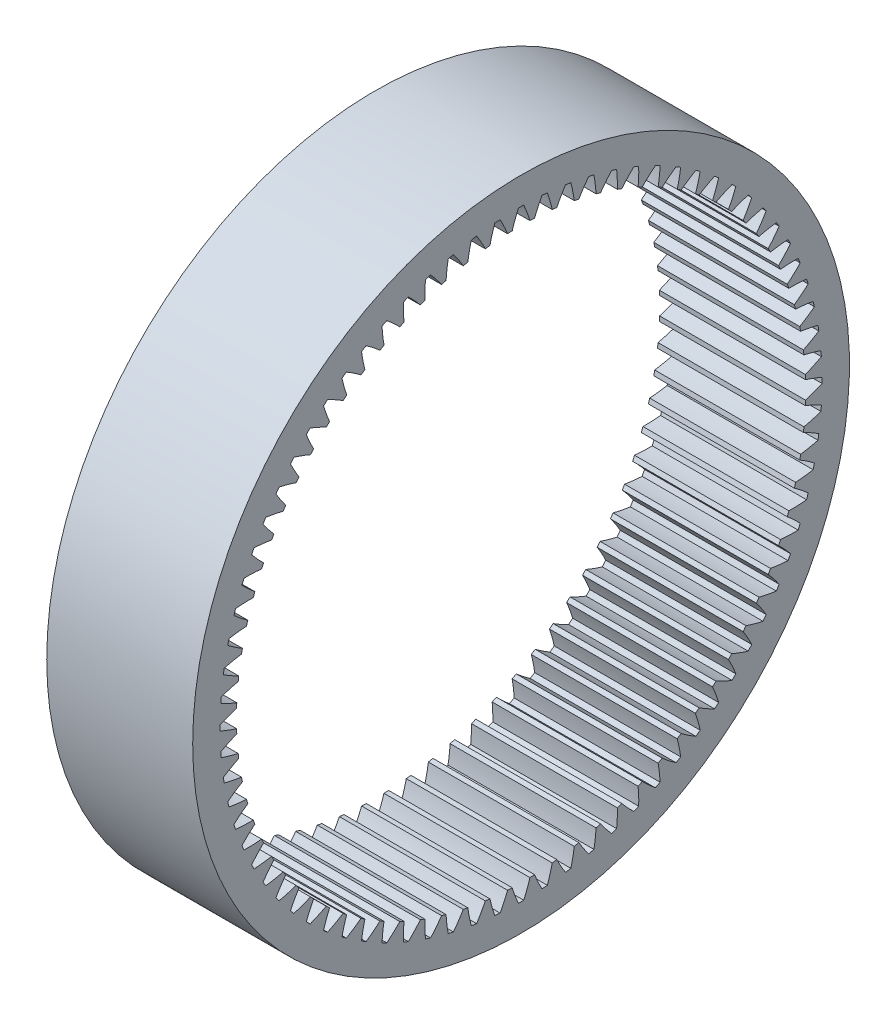
SolidWorks part; units mm, degrees
ref_plane "Plane1" through (0, 0, 0) normal (0, 0, 1) x (1, 0, 0)
ref_plane "Plane2" through (0, 0, 0) normal (0, 1, 0) x (1, 0, 0)
ref_plane "Plane3" through (0, 0, 0) normal (1, 0, 0) x (0, 0, -1)
other "Configuration Table"
sketch "HoldingSke" plane through (0, 0, 0) normal (0, 1, 0) x (1, 0, 0)
  line L0 (0, 0) -> (0.1158, -0.6565)
  line L1 (-15, 0) -> (100, 0) construction
  line L2 (0, 0) -> (-2.1039, 2.3779)
  line L3 (0, 0) -> (-11.863, 4.5341)
  line L4 (0, 0) -> (1.4996, 8.5048)
  line L5 (0, 0) -> (-23.7986, -8.8762)
  line L6 (0, 0) -> (-10.5278, -7.1032)
  line L7 (-2.1039, 2.3779) -> (3.3635, 27.1825)
  line L8 (-76.2, 3.8779) -> (-54.61, 3.8779)
  line L9 (-71.009, 38.7566) -> (-53.1078, 45.2721)
  line L10 (-76.2, 71.12) -> (104.1128, 71.12)
  line L11 (0, 0) -> (-30, 0)
  line L12 (-76.2, 101.6) -> (-76.147, 101.6)
  line L13 (24.9733, 27.94) -> (52.9518, 28.4284)
  line L14 (24.9733, 27.94) -> (24.9743, 27.94)
  line L15 (24.9733, 27.94) -> (100.4006, 29.5858)
  circle A0 centre (0, 0) radius 67.5
  circle A1 centre (0, 0) radius 12.7
  circle A2 centre (0, 0) radius 12.7
  dimension "MHD" = 25.4
  dimension "Hub_dia" = 25.4
  dimension "Diameter" = 135
  dimension "Num_teeth" = 80
  dimension "Pitch" = 0.6667
  dimension "Overall_len" = 25.4
  dimension "Show_teeth" = 80
  dimension "Thickness" = 12.7
  dimension "OAL" = 25.4001
  dimension "T_dim" = 21.59
  dimension "Ap" = 20
  dimension "H" = 19.05
  dimension "Pitch_radius" = 180.3128
  dimension "Width" = 30
  dimension "Backlash" = 0.053
  dimension "Addendum_fac" = 1
  dimension "Dedendum_fac" = 1.25
  dimension "Clearance_fac" = 0.25
  dimension "Dedendum_add" = 0.001
  dimension "Module" = 1.5
sketch "BasProSke" plane through (0, 0, 0) normal (0, 1, 0) x (1, 0, 0)
  line L0 (-10, 0) -> (60, 0) construction
  line L1 (0, 58.5) -> (0, 67.5)
  line L2 (0, 58.5) -> (30, 58.5)
  line L3 (30, 58.5) -> (30, 67.5)
  line L4 (30, 67.5) -> (0, 67.5)
  dimension "Diameter" = 135
  dimension "Thickness" = 30
  dimension "Inside_diameter" = 117
revolve "Base-Revolve" add sketch "BasProSke" angle 360 about L0
sketch "TooCutSke" plane through (0, 0, 0) normal (1, 0, 0) x (0, 0, -1)
  line L3 (1.3105, 59.9857) -> (1.3105, 53.6633) construction
  line L4 (0, 0) -> (0, 59.563) construction
  line L5 (0, 0) -> (-2.6825, 68.2748) construction
  line L6 (-26.8807, 49.7264) -> (35.8215, 52.19) construction
  circle A0 centre (0, 0) radius 60 construction
  circle A1 centre (0, 0) radius 61.876 construction
  circle A2 centre (0, 0) radius 50.7434 construction
  circle A3 centre (0, 0) radius 58.4746 construction
  arc A4 (1.8241, 58.4461) -> (0.55, 61.8736) centre (-26.8807, 49.7264) ccw
  arc A5 (1.8241, 58.4461) -> (-1.8241, 58.4461) centre (0, 0) ccw
  arc A6 (0.55, 61.8736) -> (-0.55, 61.8736) centre (0, 0) ccw
  arc A7 (-0.55, 61.8736) -> (-1.8241, 58.4461) centre (26.8807, 49.7264) ccw
  dimension "Pitch_dia" = 120
  dimension "Base_dia" = 101.4868
  dimension "Root_dia" = 123.752
  dimension "Overcut_dia" = 116.9492
  dimension "Flank_rad" = 30
  dimension "Half_ang" = 2.25
  dimension "Half_CT" = 1.3105
extrude "ToothCut" cut sketch "TooCutSke" along normal through all
fillet "Breaks" [suppressed] radius 0.15
fillet "RootFillets" [suppressed] radius 0.376
pattern_circular "TeethCuts" count 80 every 4.5 about axis through (-10, 0, 0) along (1, 0, 0) of "RootFillets", "Breaks", "ToothCut"
sketch "Эскиз1" plane through (30, 0, 0) normal (1, 0, 0) x (0, 0, -1)
  circle A0 centre (-53.6173, 36.21) radius 1.666
  dimension "D1" = 3.3321
extrude "Бобышка-Вытянуть2" add sketch "Эскиз1" against normal up to surface (30 mm away) up to face at (0, 0, 67.5)
equation "' \"Module@HoldingSke\" = 6.35"
equation "' \"Num_teeth@HoldingSke\" = 24"
equation "' \"Ap@HoldingSke\" =  14.5"
equation "' \"Ap@HoldingSke\" = 14.5"
equation "' \"Width@HoldingSke\" = 12"
equation "' \"Diameter@HoldingSke\" = 8 * 25.4"
equation "' \"Show_teeth@HoldingSke\" = 100"
equation "' \"Backlash@HoldingSke\" = 0.009 * 25.4"
equation "' \"Addendum_fac@HoldingSke\" = 1.0"
equation "' \"Dedendum_fac@HoldingSke\" = 1.25"
equation "' \"Dedendum_add@HoldingSke\" = 0.00005 * 25.4"
equation "' \"Clearance_fac@HoldingSke\" = 0.25"
equation "\"Pitch@HoldingSke\" = 1 / \"Module@HoldingSke\" "
equation "\"Overcut_dia@TooCutSke\" = (\"Num_teeth@HoldingSke\" - 2 * \"Addendum_fac@HoldingSke\") / \"Pitch@HoldingSke\" - 0.002 * 25.4"
equation "\"Pitch_dia@TooCutSke\" = \"Num_teeth@HoldingSke\" / \"Pitch@HoldingSke\""
equation "\"Base_dia@TooCutSke\" = \"Num_teeth@HoldingSke\" / \"Pitch@HoldingSke\" * cos((\"Ap@HoldingSke\"  * 3.14159265 / 180)) * 0.90"
equation "\"Root_dia@TooCutSke\" = \"Num_teeth@HoldingSke\"  / \"Pitch@HoldingSke\" + 2 *  \"Dedendum_fac@HoldingSke\"/ \"Pitch@HoldingSke\" + \"Dedendum_add@HoldingSke\" * 2"
equation "\"Half_ang@TooCutSke\" = 180 / \"Num_teeth@HoldingSke\""
equation "\"Half_CT@TooCutSke\" = \"Num_teeth@HoldingSke\" / \"Pitch@HoldingSke\" * sin((3.14159265 / 2 / \"Num_teeth@HoldingSke\")) / 2 + 10 * \"Backlash@HoldingSke\" / 4"
equation "\"Flank_rad@TooCutSke\" = \"Num_teeth@HoldingSke\" / \"Pitch@HoldingSke\" / 4"
equation "\"Radius@RootFillets\"= \"Clearance_fac@HoldingSke\" / \"Pitch@HoldingSke\" + \"Dedendum_add@HoldingSke\""
equation "\"Break_rad@Breaks\" = 0.02 / \"Pitch@HoldingSke\" * 5"
equation "\"Num_teeth@TeethCuts\" = int( \"Show_teeth@HoldingSke\" ) + 1"
equation "\"Num_teeth@TeethCuts\" = ((sgn( \"Num_teeth@TeethCuts\" - \"Num_teeth@HoldingSke\" )-1)*( \"Num_teeth@TeethCuts\" - \"Num_teeth@HoldingSke\" ))/-2+ \"Num_teeth@HoldingSke\""
equation "\"Num_teeth@TeethCuts\" = ((sgn( \"Num_teeth@TeethCuts\" - 2.0)+1)*( \"Num_teeth@TeethCuts\" - 2.0))/2 +2.0"
equation "\"Angle@TeethCuts\" = 360.0 / \"Num_teeth@HoldingSke\""
equation "\"Diameter@BasProSke\" = \"Num_teeth@HoldingSke\"  / \"Pitch@HoldingSke\" + 2 *  \"Dedendum_fac@HoldingSke\"/ \"Pitch@HoldingSke\" + \"Dedendum_add@HoldingSke\" * 2 + 0.002 * 25.4"
equation "\"Diameter@BasProSke\" = ((sgn( \"Diameter@BasProSke\"  - \"Diameter@HoldingSke\" )+1)*( \"Diameter@BasProSke\"  - \"Diameter@HoldingSke\" ))/2 + \"Diameter@HoldingSke\""
equation "\"Inside_diameter@BasProSke\" =  (\"Num_teeth@HoldingSke\" - 2 * \"Addendum_fac@HoldingSke\") / \"Pitch@HoldingSke\" "
equation "\"Thickness@BasProSke\"  = \"Width@HoldingSke\""
